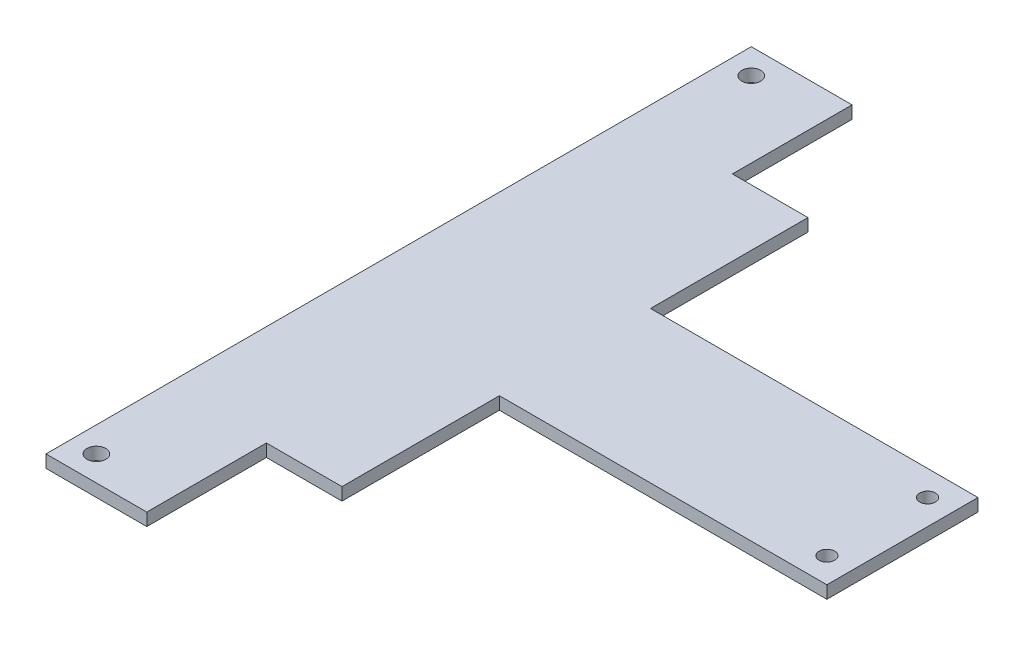
SolidWorks part; units mm, degrees
ref_plane "Front Plane" through (0, 0, 0) normal (0, 0, 1) x (1, 0, 0)
ref_plane "Top Plane" through (0, 0, 0) normal (0, 1, 0) x (1, 0, 0)
ref_plane "Right Plane" through (0, 0, 0) normal (1, 0, 0) x (0, 0, -1)
sketch "Sketch1" plane through (0, 0, 0) normal (0, 1, 0) x (1, 0, 0)
  line L0 (0, -177.8) -> (0, 177.8)
  line L1 (0, 177.8) -> (38.1, 177.8)
  line L2 (38.1, 177.8) -> (38.1, -177.8)
  line L3 (38.1, -177.8) -> (0, -177.8)
  line L4 (38.1, -38.1) -> (203.2, -38.1)
  line L5 (203.2, -38.1) -> (203.2, 38.1)
  line L6 (203.2, 38.1) -> (38.1, 38.1)
  line L7 (38.1, 38.1) -> (38.1, -38.1)
  line L8 (0, 0) -> (203.2, 0) construction
  dimension "D1" = 203.2
  dimension "D2" = 355.6
  dimension "D3" = 38.1
  dimension "D4" = 76.2
extrude "Boss-Extrude1" add sketch "Sketch1" along normal mid plane 6.35 contours L8 L0 L3 L2 L7 | L8 L7 L4 L5 | L2 L8 L5 L6 | L0 L8 L2 L1
hole_wizard "1/4 (0.25) Diameter Hole1" positions "Sketch2" profile "Sketch3" hole size "1/4" standard "ANSI Inch" end condition through all
sketch "Sketch2" plane through (0, 3.175, 0) normal (0, 1, 0) x (1, 0, 0)
  line L0 (203.2, 38.1) -> (38.1, 38.1) construction
  line L1 (38.1, -38.1) -> (203.2, -38.1) construction
  line L2 (203.2, -38.1) -> (203.2, 38.1) construction
  point P0 (190.5, 25.4)
  point P2 (190.5, -25.4)
  dimension "D1" = 12.7
  dimension "D2" = 12.7
  dimension "D3" = 12.7
sketch "Sketch3" plane through (190.5, 3.175, -25.4) normal (1, 0, 0) x (0, 0, 1)
  line L0 (0, 0) -> (0, 6.35)
  line L1 (0, 6.35) -> (3.9687, 6.35)
  line L2 (3.9687, 6.35) -> (3.9687, 0)
  line L5 (3.9687, 0) -> (0, 0)
  line L11 (0, -6.35) -> (0, 107.95) construction
  dimension "Thru Hole Dia." = 7.9375
  dimension "Thru Hole Depth" = 6.35
sketch "Sketch4" plane through (0, -3.175, 0) normal (0, -1, 0) x (1, 0, 0)
  line L0 (38.1, 177.8) -> (0, 177.8) construction
  line L8 (0, 177.8) -> (-50.8, 177.8)
  line L9 (-50.8, 177.8) -> (-50.8, -177.8)
  line L10 (-50.8, -177.8) -> (0, -177.8)
  line L11 (0, -177.8) -> (0, 177.8)
  circle A1 centre (-38.1, -165.1) radius 4.7625
  circle A3 centre (-38.1, 165.1) radius 4.7625
  point P5 (0, -203.2)
  point P8 (0, 203.2)
  point P13 (0, 203.2)
  point P14 (0, 203.2)
  dimension "D4" = 9.525
  dimension "D7" = 9.525
  dimension "D1" = 50.8
  dimension "D2" = 12.7
  dimension "D3" = 12.7
  dimension "D5" = 12.7
  dimension "D6" = 12.7
extrude "Boss-Extrude2" add sketch "Sketch4" against normal blind 6.35
sketch "Sketch5" plane through (0, -3.175, 0) normal (0, -1, 0) x (1, 0, 0)
  line L1 (38.1, 177.8) -> (0, 177.8)
  line L2 (38.1, 177.8) -> (38.1, 117.475)
  line L3 (38.1, 117.475) -> (0, 117.475)
  line L4 (0, 177.8) -> (0, 117.475)
  line L5 (38.1, -177.8) -> (0, -177.8)
  line L6 (38.1, -177.8) -> (38.1, -117.475)
  line L7 (38.1, -117.475) -> (0, -117.475)
  line L8 (0, -177.8) -> (0, -117.475)
  dimension "D1" = 38.1
  dimension "D2" = 234.95
extrude "Cut-Extrude1" cut sketch "Sketch5" against normal up to next
